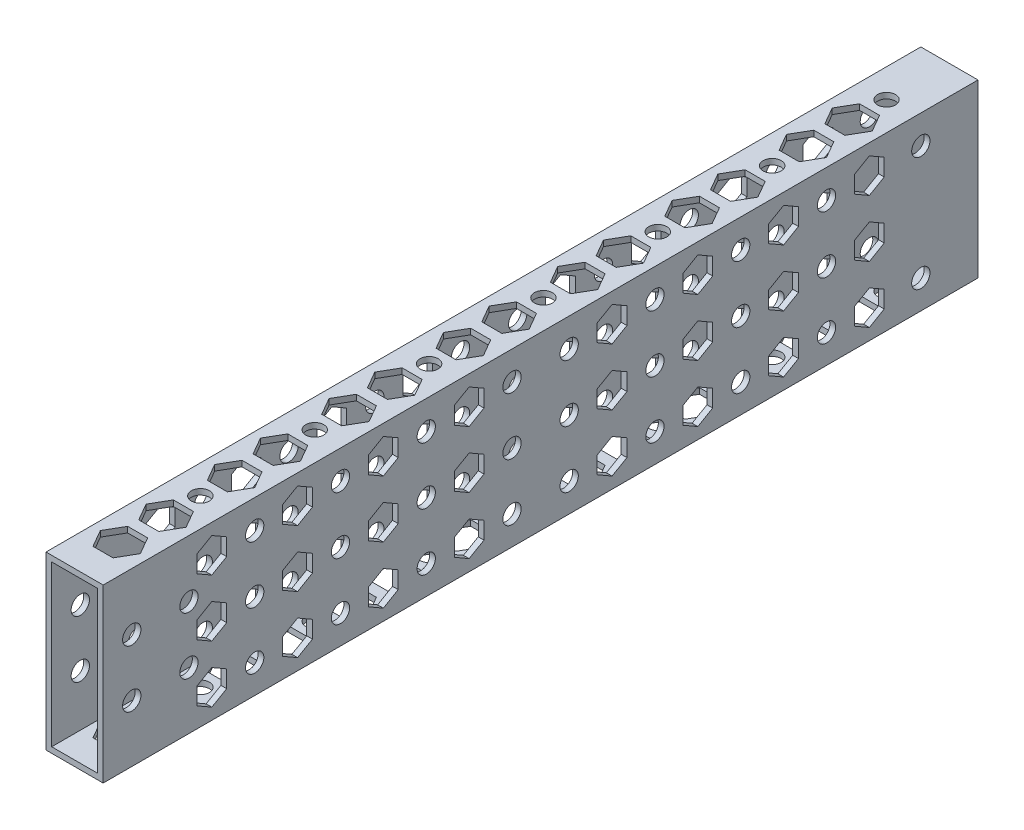
SolidWorks part; units mm, degrees
ref_plane "前视基准面" through (0, 0, 0) normal (0, 0, 1) x (1, 0, 0)
ref_plane "上视基准面" through (0, 0, 0) normal (0, 1, 0) x (1, 0, 0)
ref_plane "右视基准面" through (0, 0, 0) normal (1, 0, 0) x (0, 0, -1)
other "Configuration Table"
sketch "草图1" plane through (0, 0, 0) normal (0, 0, 1) x (1, 0, 0)
  line L1 (0, 0) -> (10, 0)
  line L2 (0, 0) -> (0, -30)
  line L3 (0, -30) -> (10, -30)
  line L4 (10, 0) -> (10, -30)
  dimension "D1" = 10
  dimension "D2" = 30
extrude "拉伸-薄壁1" add sketch "草图1" along normal blind 153 thin
sketch "草图2" plane through (0, -30, 0) normal (0, -1, 0) x (1, 0, 0)
  line L0 (0, 10) -> (10, 10) construction
  line L1 (10, 153) -> (10, 0) construction
  line L2 (0, 153) -> (0, 0) construction
  line L3 (5, 10) -> (5, 0) construction
  line L4 (0, 0) -> (10, 0) construction
  line L5 (10, 21) -> (0, 21) construction
  line L6 (3.25, 20.0311) -> (1.5, 17)
  line L7 (1.5, 17) -> (3.25, 13.9689)
  line L8 (3.25, 13.9689) -> (6.75, 13.9689)
  line L9 (6.75, 13.9689) -> (8.5, 17)
  line L10 (8.5, 17) -> (6.75, 20.0311)
  line L11 (6.75, 20.0311) -> (3.25, 20.0311)
  line L12 (6.75, 21.9689) -> (3.25, 21.9689)
  line L13 (8.5, 25) -> (6.75, 21.9689)
  line L14 (6.75, 28.0311) -> (8.5, 25)
  line L15 (3.25, 28.0311) -> (6.75, 28.0311)
  line L16 (1.5, 25) -> (3.25, 28.0311)
  line L17 (3.25, 21.9689) -> (1.5, 25)
  line L18 (3.25, 33.9689) -> (6.75, 33.9689)
  line L19 (6.75, 33.9689) -> (8.5, 37)
  line L20 (8.5, 37) -> (6.75, 40.0311)
  line L21 (3.25, 40.0311) -> (1.5, 37)
  line L22 (6.75, 40.0311) -> (3.25, 40.0311)
  line L23 (1.5, 37) -> (3.25, 33.9689)
  line L24 (6.75, 41.9689) -> (3.25, 41.9689)
  line L25 (8.5, 45) -> (6.75, 41.9689)
  line L26 (6.75, 48.0311) -> (8.5, 45)
  line L27 (3.25, 48.0311) -> (6.75, 48.0311)
  line L28 (1.5, 45) -> (3.25, 48.0311)
  line L29 (3.25, 41.9689) -> (1.5, 45)
  line L30 (3.25, 53.9689) -> (6.75, 53.9689)
  line L31 (6.75, 53.9689) -> (8.5, 57)
  line L32 (8.5, 57) -> (6.75, 60.0311)
  line L33 (3.25, 60.0311) -> (1.5, 57)
  line L34 (6.75, 60.0311) -> (3.25, 60.0311)
  line L35 (1.5, 57) -> (3.25, 53.9689)
  line L36 (6.75, 61.9689) -> (3.25, 61.9689)
  line L37 (8.5, 65) -> (6.75, 61.9689)
  line L38 (6.75, 68.0311) -> (8.5, 65)
  line L39 (3.25, 68.0311) -> (6.75, 68.0311)
  line L40 (1.5, 65) -> (3.25, 68.0311)
  line L41 (3.25, 61.9689) -> (1.5, 65)
  line L42 (3.25, 73.9689) -> (6.75, 73.9689)
  line L43 (6.75, 73.9689) -> (8.5, 77)
  line L44 (8.5, 77) -> (6.75, 80.0311)
  line L45 (3.25, 80.0311) -> (1.5, 77)
  line L46 (6.75, 80.0311) -> (3.25, 80.0311)
  line L47 (1.5, 77) -> (3.25, 73.9689)
  line L48 (6.75, 81.9689) -> (3.25, 81.9689)
  line L49 (8.5, 85) -> (6.75, 81.9689)
  line L50 (6.75, 88.0311) -> (8.5, 85)
  line L51 (3.25, 88.0311) -> (6.75, 88.0311)
  line L52 (1.5, 85) -> (3.25, 88.0311)
  line L53 (3.25, 81.9689) -> (1.5, 85)
  line L54 (3.25, 93.9689) -> (6.75, 93.9689)
  line L55 (6.75, 93.9689) -> (8.5, 97)
  line L56 (8.5, 97) -> (6.75, 100.0311)
  line L57 (3.25, 100.0311) -> (1.5, 97)
  line L58 (6.75, 100.0311) -> (3.25, 100.0311)
  line L59 (1.5, 97) -> (3.25, 93.9689)
  line L60 (6.75, 101.9689) -> (3.25, 101.9689)
  line L61 (8.5, 105) -> (6.75, 101.9689)
  line L62 (6.75, 108.0311) -> (8.5, 105)
  line L63 (3.25, 108.0311) -> (6.75, 108.0311)
  line L64 (1.5, 105) -> (3.25, 108.0311)
  line L65 (3.25, 101.9689) -> (1.5, 105)
  line L66 (3.25, 113.9689) -> (6.75, 113.9689)
  line L67 (6.75, 113.9689) -> (8.5, 117)
  line L68 (8.5, 117) -> (6.75, 120.0311)
  line L69 (3.25, 120.0311) -> (1.5, 117)
  line L70 (6.75, 120.0311) -> (3.25, 120.0311)
  line L71 (1.5, 117) -> (3.25, 113.9689)
  line L72 (6.75, 121.9689) -> (3.25, 121.9689)
  line L73 (8.5, 125) -> (6.75, 121.9689)
  line L74 (6.75, 128.0311) -> (8.5, 125)
  line L75 (3.25, 128.0311) -> (6.75, 128.0311)
  line L76 (1.5, 125) -> (3.25, 128.0311)
  line L77 (3.25, 121.9689) -> (1.5, 125)
  line L78 (3.25, 133.9689) -> (6.75, 133.9689)
  line L79 (6.75, 133.9689) -> (8.5, 137)
  line L80 (8.5, 137) -> (6.75, 140.0311)
  line L81 (3.25, 140.0311) -> (1.5, 137)
  line L82 (6.75, 140.0311) -> (3.25, 140.0311)
  line L83 (1.5, 137) -> (3.25, 133.9689)
  line L84 (6.75, 141.9689) -> (3.25, 141.9689)
  line L85 (8.5, 145) -> (6.75, 141.9689)
  line L86 (6.75, 148.0311) -> (8.5, 145)
  line L87 (3.25, 148.0311) -> (6.75, 148.0311)
  line L88 (1.5, 145) -> (3.25, 148.0311)
  line L89 (3.25, 141.9689) -> (1.5, 145)
  circle A4 centre (5, 11) radius 1.575
  circle A5 centre (5, 31) radius 1.575
  circle A6 centre (5, 51) radius 1.575
  circle A7 centre (5, 71) radius 1.575
  circle A8 centre (5, 91) radius 1.575
  circle A9 centre (5, 111) radius 1.575
  circle A10 centre (5, 131) radius 1.575
  circle A14 centre (5, 17) radius 3.0311 construction
  circle A15 centre (5, 25) radius 3.0311 construction
  circle A16 centre (5, 45) radius 3.0311 construction
  circle A17 centre (5, 37) radius 3.0311 construction
  circle A18 centre (5, 65) radius 3.0311 construction
  circle A19 centre (5, 57) radius 3.0311 construction
  circle A20 centre (5, 85) radius 3.0311 construction
  circle A21 centre (5, 77) radius 3.0311 construction
  circle A22 centre (5, 105) radius 3.0311 construction
  circle A23 centre (5, 97) radius 3.0311 construction
  circle A24 centre (5, 125) radius 3.0311 construction
  circle A25 centre (5, 117) radius 3.0311 construction
  circle A26 centre (5, 145) radius 3.0311 construction
  circle A27 centre (5, 137) radius 3.0311 construction
  dimension "D2" = 3.5
  dimension "D5" = 3.15
  dimension "D1" = 10
  dimension "D3" = 6
  dimension "D4" = 10
  dimension "D6" = 11
  dimension "D8" = 20
  dimension "D9" = 7
  dimension "D10" = 20
  dimension "D7" = 7
extrude "切除-拉伸1" cut sketch "草图2" against normal through all
sketch "草图3" plane through (0, 0, 0) normal (-1, 0, 0) x (0, 0, 1)
  line L0 (143, 0) -> (143, -30) construction
  line L1 (153, 0) -> (0, 0) construction
  line L2 (153, -30) -> (0, -30) construction
  line L3 (153, 0) -> (153, -30) construction
  line L4 (143, -15) -> (153, -15) construction
  line L5 (76.5, 0) -> (76.5, -30) construction
  line L6 (10, -15) -> (0, -15) construction
  line L7 (10, 0) -> (10, -30) construction
  line L8 (71.5, -5) -> (56.5, -5) construction
  line L9 (64, -12) -> (61.4019, -13.5)
  line L10 (64, -2) -> (61.4019, -3.5)
  line L11 (61.4019, -3.5) -> (61.4019, -6.5)
  line L12 (61.4019, -6.5) -> (64, -8)
  line L13 (64, -8) -> (66.5981, -6.5)
  line L14 (66.5981, -6.5) -> (66.5981, -3.5)
  line L15 (66.5981, -3.5) -> (64, -2)
  line L16 (66.5981, -16.5) -> (66.5981, -13.5)
  line L17 (66.5981, -13.5) -> (64, -12)
  line L18 (64, -18) -> (66.5981, -16.5)
  line L19 (61.4019, -16.5) -> (64, -18)
  line L20 (61.4019, -13.5) -> (61.4019, -16.5)
  line L21 (64, -22) -> (61.4019, -23.5)
  line L22 (66.5981, -26.5) -> (66.5981, -23.5)
  line L23 (66.5981, -23.5) -> (64, -22)
  line L24 (64, -28) -> (66.5981, -26.5)
  line L25 (61.4019, -26.5) -> (64, -28)
  line L26 (61.4019, -23.5) -> (61.4019, -26.5)
  line L27 (49, -2) -> (46.4019, -3.5)
  line L28 (51.5981, -3.5) -> (49, -2)
  line L29 (51.5981, -6.5) -> (51.5981, -3.5)
  line L30 (49, -8) -> (51.5981, -6.5)
  line L31 (46.4019, -6.5) -> (49, -8)
  line L32 (46.4019, -3.5) -> (46.4019, -6.5)
  line L33 (49, -12) -> (46.4019, -13.5)
  line L34 (51.5981, -13.5) -> (49, -12)
  line L35 (51.5981, -16.5) -> (51.5981, -13.5)
  line L36 (49, -18) -> (51.5981, -16.5)
  line L37 (46.4019, -16.5) -> (49, -18)
  line L38 (46.4019, -13.5) -> (46.4019, -16.5)
  line L39 (51.5981, -23.5) -> (49, -22)
  line L40 (49, -22) -> (46.4019, -23.5)
  line L41 (46.4019, -23.5) -> (46.4019, -26.5)
  line L42 (51.5981, -26.5) -> (51.5981, -23.5)
  line L43 (49, -28) -> (51.5981, -26.5)
  line L44 (46.4019, -26.5) -> (49, -28)
  line L45 (34, -2) -> (31.4019, -3.5)
  line L46 (36.5981, -3.5) -> (34, -2)
  line L47 (36.5981, -6.5) -> (36.5981, -3.5)
  line L48 (34, -8) -> (36.5981, -6.5)
  line L49 (31.4019, -6.5) -> (34, -8)
  line L50 (31.4019, -3.5) -> (31.4019, -6.5)
  line L51 (34, -12) -> (31.4019, -13.5)
  line L52 (36.5981, -13.5) -> (34, -12)
  line L53 (36.5981, -16.5) -> (36.5981, -13.5)
  line L54 (34, -18) -> (36.5981, -16.5)
  line L55 (31.4019, -16.5) -> (34, -18)
  line L56 (31.4019, -13.5) -> (31.4019, -16.5)
  line L57 (36.5981, -23.5) -> (34, -22)
  line L58 (34, -22) -> (31.4019, -23.5)
  line L59 (31.4019, -23.5) -> (31.4019, -26.5)
  line L60 (36.5981, -26.5) -> (36.5981, -23.5)
  line L61 (34, -28) -> (36.5981, -26.5)
  line L62 (31.4019, -26.5) -> (34, -28)
  line L63 (19, -2) -> (16.4019, -3.5)
  line L64 (21.5981, -3.5) -> (19, -2)
  line L65 (21.5981, -6.5) -> (21.5981, -3.5)
  line L66 (19, -8) -> (21.5981, -6.5)
  line L67 (16.4019, -6.5) -> (19, -8)
  line L68 (16.4019, -3.5) -> (16.4019, -6.5)
  line L69 (19, -12) -> (16.4019, -13.5)
  line L70 (21.5981, -13.5) -> (19, -12)
  line L71 (21.5981, -16.5) -> (21.5981, -13.5)
  line L72 (19, -18) -> (21.5981, -16.5)
  line L73 (16.4019, -16.5) -> (19, -18)
  line L74 (16.4019, -13.5) -> (16.4019, -16.5)
  line L75 (21.5981, -23.5) -> (19, -22)
  line L76 (19, -22) -> (16.4019, -23.5)
  line L77 (16.4019, -23.5) -> (16.4019, -26.5)
  line L78 (21.5981, -26.5) -> (21.5981, -23.5)
  line L79 (19, -28) -> (21.5981, -26.5)
  line L80 (16.4019, -26.5) -> (19, -28)
  line L81 (81.5, -5) -> (96.5, -5) construction
  line L82 (136.5981, -26.5) -> (134, -28)
  line L83 (134, -28) -> (131.4019, -26.5)
  line L84 (131.4019, -26.5) -> (131.4019, -23.5)
  line L85 (136.5981, -23.5) -> (136.5981, -26.5)
  line L86 (134, -22) -> (136.5981, -23.5)
  line L87 (131.4019, -23.5) -> (134, -22)
  line L88 (136.5981, -13.5) -> (136.5981, -16.5)
  line L89 (136.5981, -16.5) -> (134, -18)
  line L90 (134, -18) -> (131.4019, -16.5)
  line L91 (131.4019, -16.5) -> (131.4019, -13.5)
  line L92 (131.4019, -13.5) -> (134, -12)
  line L93 (134, -12) -> (136.5981, -13.5)
  line L94 (136.5981, -3.5) -> (136.5981, -6.5)
  line L95 (136.5981, -6.5) -> (134, -8)
  line L96 (134, -8) -> (131.4019, -6.5)
  line L97 (131.4019, -6.5) -> (131.4019, -3.5)
  line L98 (131.4019, -3.5) -> (134, -2)
  line L99 (134, -2) -> (136.5981, -3.5)
  line L100 (121.5981, -26.5) -> (119, -28)
  line L101 (119, -28) -> (116.4019, -26.5)
  line L102 (116.4019, -26.5) -> (116.4019, -23.5)
  line L103 (121.5981, -23.5) -> (121.5981, -26.5)
  line L104 (119, -22) -> (121.5981, -23.5)
  line L105 (116.4019, -23.5) -> (119, -22)
  line L106 (121.5981, -13.5) -> (121.5981, -16.5)
  line L107 (121.5981, -16.5) -> (119, -18)
  line L108 (119, -18) -> (116.4019, -16.5)
  line L109 (116.4019, -16.5) -> (116.4019, -13.5)
  line L110 (116.4019, -13.5) -> (119, -12)
  line L111 (119, -12) -> (121.5981, -13.5)
  line L112 (121.5981, -3.5) -> (121.5981, -6.5)
  line L113 (121.5981, -6.5) -> (119, -8)
  line L114 (119, -8) -> (116.4019, -6.5)
  line L115 (116.4019, -6.5) -> (116.4019, -3.5)
  line L116 (116.4019, -3.5) -> (119, -2)
  line L117 (119, -2) -> (121.5981, -3.5)
  line L118 (106.5981, -26.5) -> (104, -28)
  line L119 (104, -28) -> (101.4019, -26.5)
  line L120 (101.4019, -26.5) -> (101.4019, -23.5)
  line L121 (106.5981, -23.5) -> (106.5981, -26.5)
  line L122 (104, -22) -> (106.5981, -23.5)
  line L123 (101.4019, -23.5) -> (104, -22)
  line L124 (106.5981, -13.5) -> (106.5981, -16.5)
  line L125 (106.5981, -16.5) -> (104, -18)
  line L126 (104, -18) -> (101.4019, -16.5)
  line L127 (101.4019, -16.5) -> (101.4019, -13.5)
  line L128 (101.4019, -13.5) -> (104, -12)
  line L129 (104, -12) -> (106.5981, -13.5)
  line L130 (106.5981, -3.5) -> (106.5981, -6.5)
  line L131 (106.5981, -6.5) -> (104, -8)
  line L132 (104, -8) -> (101.4019, -6.5)
  line L133 (101.4019, -6.5) -> (101.4019, -3.5)
  line L134 (101.4019, -3.5) -> (104, -2)
  line L135 (104, -2) -> (106.5981, -3.5)
  line L136 (91.5981, -23.5) -> (91.5981, -26.5)
  line L137 (91.5981, -26.5) -> (89, -28)
  line L138 (89, -28) -> (86.4019, -26.5)
  line L139 (86.4019, -23.5) -> (89, -22)
  line L140 (86.4019, -26.5) -> (86.4019, -23.5)
  line L141 (89, -22) -> (91.5981, -23.5)
  line L142 (91.5981, -13.5) -> (91.5981, -16.5)
  line L143 (91.5981, -16.5) -> (89, -18)
  line L144 (89, -18) -> (86.4019, -16.5)
  line L145 (86.4019, -13.5) -> (89, -12)
  line L146 (86.4019, -16.5) -> (86.4019, -13.5)
  line L147 (86.4019, -3.5) -> (89, -2)
  line L148 (86.4019, -6.5) -> (86.4019, -3.5)
  line L149 (89, -8) -> (86.4019, -6.5)
  line L150 (91.5981, -6.5) -> (89, -8)
  line L151 (91.5981, -3.5) -> (91.5981, -6.5)
  line L152 (89, -2) -> (91.5981, -3.5)
  line L153 (89, -12) -> (91.5981, -13.5)
  circle A0 centre (148, -10) radius 1.6
  circle A1 centre (148, -20) radius 1.6
  circle A2 centre (138, -20) radius 1.6
  circle A3 centre (138, -10) radius 1.6
  circle A8 centre (10, -5) radius 1.6
  circle A9 centre (10, -25) radius 1.6
  circle A10 centre (71.5, -5) radius 1.6
  circle A11 centre (71.5, -15) radius 1.6
  circle A12 centre (71.5, -25) radius 1.6
  circle A13 centre (56.5, -5) radius 1.6
  circle A14 centre (56.5, -15) radius 1.6
  circle A15 centre (56.5, -25) radius 1.6
  circle A16 centre (41.5, -5) radius 1.6
  circle A17 centre (41.5, -15) radius 1.6
  circle A18 centre (41.5, -25) radius 1.6
  circle A19 centre (26.5, -5) radius 1.6
  circle A20 centre (26.5, -15) radius 1.6
  circle A21 centre (26.5, -25) radius 1.6
  circle A22 centre (64, -5) radius 2.5981 construction
  circle A23 centre (64, -15) radius 2.5981 construction
  circle A24 centre (64, -25) radius 2.5981 construction
  circle A25 centre (49, -5) radius 2.5981 construction
  circle A26 centre (49, -15) radius 2.5981 construction
  circle A27 centre (49, -25) radius 2.5981 construction
  circle A28 centre (34, -5) radius 2.5981 construction
  circle A29 centre (34, -15) radius 2.5981 construction
  circle A30 centre (34, -25) radius 2.5981 construction
  circle A31 centre (19, -5) radius 2.5981 construction
  circle A32 centre (19, -15) radius 2.5981 construction
  circle A33 centre (19, -25) radius 2.5981 construction
  circle A34 centre (134, -25) radius 2.5981 construction
  circle A35 centre (134, -15) radius 2.5981 construction
  circle A36 centre (134, -5) radius 2.5981 construction
  circle A37 centre (119, -25) radius 2.5981 construction
  circle A38 centre (119, -15) radius 2.5981 construction
  circle A39 centre (119, -5) radius 2.5981 construction
  circle A40 centre (104, -25) radius 2.5981 construction
  circle A41 centre (104, -15) radius 2.5981 construction
  circle A42 centre (104, -5) radius 2.5981 construction
  circle A43 centre (89, -25) radius 2.5981 construction
  circle A44 centre (89, -15) radius 2.5981 construction
  circle A45 centre (89, -5) radius 2.5981 construction
  circle A46 centre (126.5, -25) radius 1.6
  circle A47 centre (126.5, -15) radius 1.6
  circle A48 centre (126.5, -5) radius 1.6
  circle A49 centre (111.5, -25) radius 1.6
  circle A50 centre (111.5, -15) radius 1.6
  circle A51 centre (111.5, -5) radius 1.6
  circle A52 centre (96.5, -25) radius 1.6
  circle A53 centre (96.5, -15) radius 1.6
  circle A54 centre (96.5, -5) radius 1.6
  circle A55 centre (81.5, -25) radius 1.6
  circle A56 centre (81.5, -15) radius 1.6
  circle A57 centre (81.5, -5) radius 1.6
  dimension "D2" = 3.2
  dimension "D5" = 3.2
  dimension "D7" = 3.2
  dimension "D1" = 10
  dimension "D3" = 5
  dimension "D4" = 5
  dimension "D6" = 5
  dimension "D8" = 5
  dimension "D9" = 5
  dimension "D10" = 10
  dimension "D12" = 15
  dimension "D13" = 3
  dimension "D14" = 7.5
  dimension "D16" = 10
  dimension "D17" = 4
  dimension "D18" = 15
  dimension "D11" = 3
  dimension "D15" = 3
extrude "切除-拉伸2" cut sketch "草图3" against normal through all
